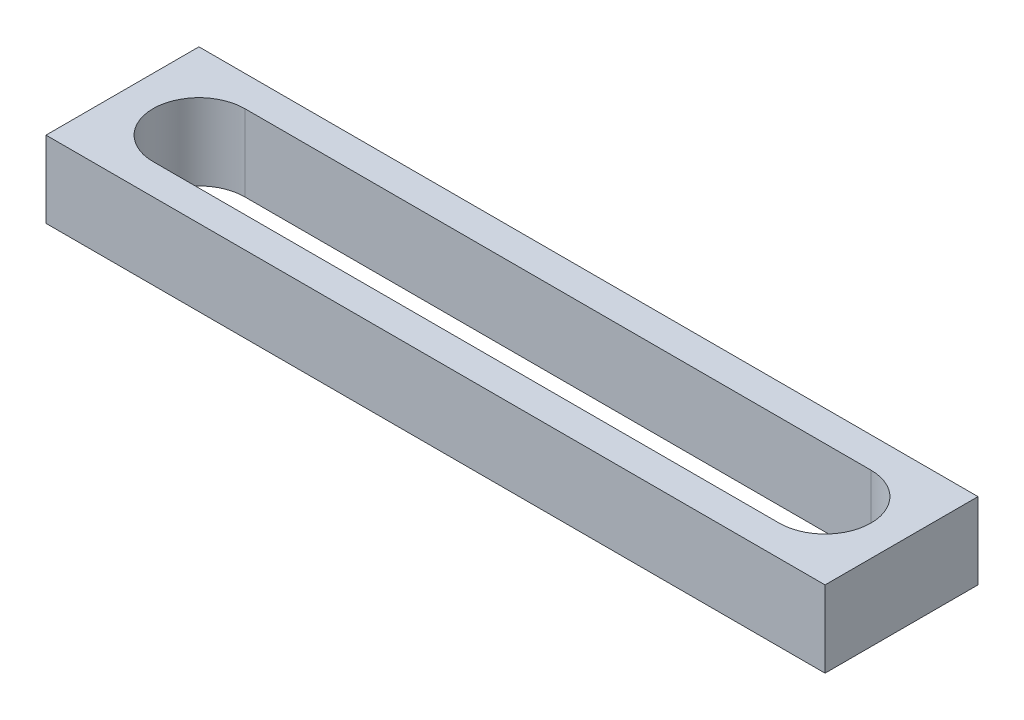
SolidWorks part; units mm, degrees
ref_plane "Front Plane" through (0, 0, 0) normal (0, 0, 1) x (1, 0, 0)
ref_plane "Top Plane" through (0, 0, 0) normal (0, 1, 0) x (1, 0, 0)
ref_plane "Right Plane" through (0, 0, 0) normal (1, 0, 0) x (0, 0, -1)
sketch "Sketch1" plane through (0, 0, 0) normal (0, 1, 0) x (1, 0, 0)
  line L11 (0, 13.2272) -> (0, -10.6493) construction
  line L14 (0, 0) -> (-50.94, 0)
  line L15 (0, 0) -> (0, 10)
  line L16 (0, 10) -> (-50.94, 10)
  line L17 (-50.94, 0) -> (-50.94, 10)
  dimension "D2" = 50.94
  dimension "D1" = 10
extrude "Boss-Extrude1" add sketch "Sketch1" along normal blind 5 contours L17 L16 L15 L14
sketch "Sketch2" plane through (0, 5, 0) normal (0, 1, 0) x (1, 0, 0)
  line L0 (-25.47, 10) -> (-25.47, -8.3904) construction
  line L1 (0, 10) -> (-50.94, 10) construction
  line L2 (-45.94, 2) -> (-5, 2)
  line L3 (-45.94, 8) -> (-5, 8)
  arc A0 (-45.94, 8) -> (-45.94, 2) centre (-45.94, 5) ccw
  arc A1 (-5, 8) -> (-5, 2) centre (-5, 5) cw
  dimension "D1" = 6
  dimension "D2" = 5
  dimension "D3" = 5
extrude "Cut-Extrude1" cut sketch "Sketch2" against normal through all
